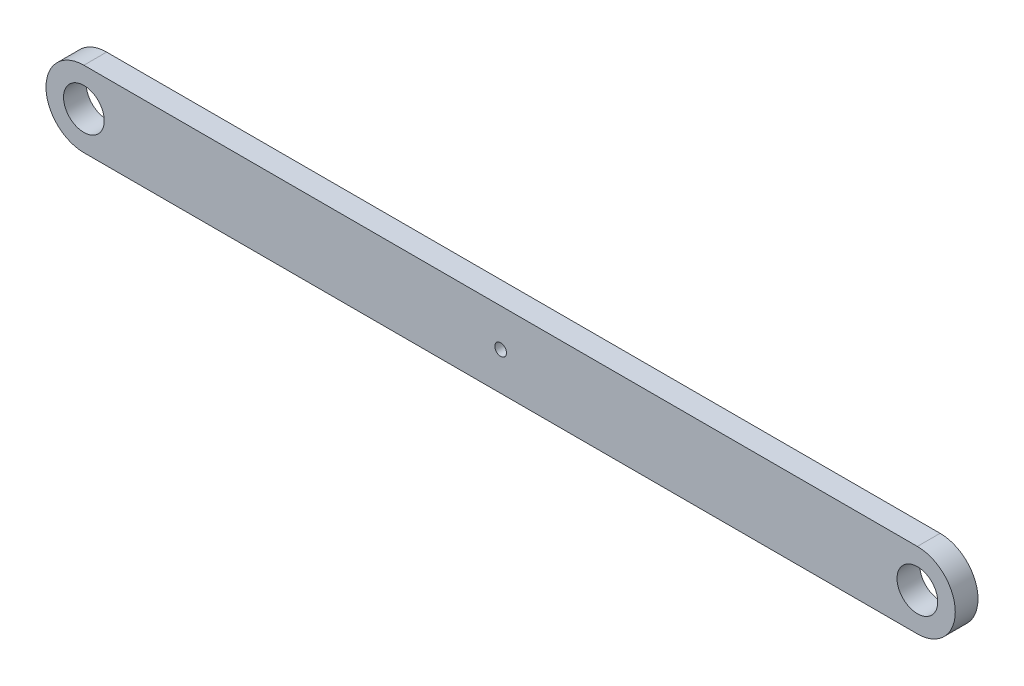
SolidWorks part; units mm, degrees
ref_plane "Plan de face" through (0, 0, 0) normal (0, 0, 1) x (1, 0, 0)
ref_plane "Plan de dessus" through (0, 0, 0) normal (0, 1, 0) x (1, 0, 0)
ref_plane "Plan de droite" through (0, 0, 0) normal (1, 0, 0) x (0, 0, -1)
sketch "Esquisse1" plane through (0, 0, 0) normal (0, 0, 1) x (1, 0, 0)
  line L0 (0, 0) -> (220, 0)
  line L2 (220, 20) -> (0, 20)
  line L4 (0, 10) -> (220, 10) construction
  arc A0 (0, 20) -> (0, 0) centre (0, 10) ccw
  arc A1 (220, 20) -> (220, 0) centre (220, 10) cw
  circle A2 centre (0, 10) radius 5.375
  circle A3 centre (220, 10) radius 5.375
  circle A4 centre (110, 10) radius 1.55
  dimension "D3" = 10.75
  dimension "D4" = 10.75
  dimension "D5" = 3.1
  dimension "D1" = 220
  dimension "D2" = 20
extrude "Boss.-Extru.1" add sketch "Esquisse1" along normal blind 6
